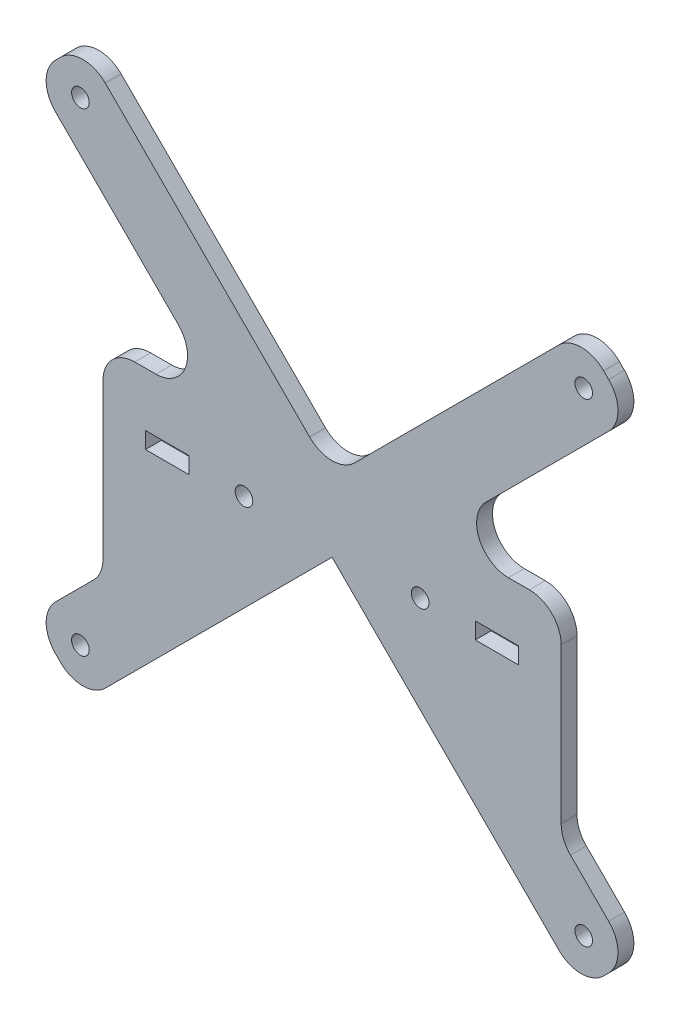
SolidWorks part; units mm, degrees
ref_plane "Front Plane" through (0, 0, 0) normal (0, 0, 1) x (1, 0, 0)
ref_plane "Top Plane" through (0, 0, 0) normal (0, 1, 0) x (1, 0, 0)
ref_plane "Right Plane" through (0, 0, 0) normal (1, 0, 0) x (0, 0, -1)
sketch "Sketch1" plane through (0, 0, 0) normal (0, 0, 1) x (1, 0, 0)
  line L0 (0, -10) -> (-70.7107, -80.7107)
  line L1 (-65, 10) -> (65, 10)
  line L2 (-65, 10) -> (-65, -10)
  line L3 (-65, -10) -> (65, -10)
  line L4 (65, 10) -> (65, -10)
  line L5 (-65, 10) -> (65, -10) construction
  line L6 (-65, -10) -> (65, 10) construction
  line L7 (0, -55) -> (0, 55) construction
  line L8 (-70.7107, -80.7107) -> (-84.8528, -66.5685)
  line L9 (-84.8528, -66.5685) -> (-28.2843, -10)
  line L10 (70.7107, -80.7107) -> (84.8528, -66.5685)
  line L11 (0, -10) -> (70.7107, -80.7107)
  line L12 (84.8528, -66.5685) -> (28.2843, -10)
  line L13 (55, 0) -> (-55, 0) construction
  line L14 (84.8528, 66.5685) -> (28.2843, 10)
  line L15 (0, 10) -> (70.7107, 80.7107)
  line L16 (-84.8528, 66.5685) -> (-28.2843, 10)
  line L17 (0, 10) -> (-70.7107, 80.7107)
  line L18 (70.7107, 80.7107) -> (84.8528, 66.5685)
  line L19 (-70.7107, 80.7107) -> (-84.8528, 66.5685)
  line L20 (-65, -10) -> (-65, -46.7157)
  line L21 (-52.95, -5.3) -> (-40.65, -5.3)
  line L22 (-52.95, -5.3) -> (-52.95, -10)
  line L23 (-52.95, -10) -> (-40.65, -10)
  line L24 (-40.65, -5.3) -> (-40.65, -10)
  line L25 (-52.95, -5.3) -> (-40.65, -10) construction
  line L26 (-52.95, -10) -> (-40.65, -5.3) construction
  line L27 (-6.15, -5.3) -> (6.15, -5.3)
  line L28 (-6.15, -5.3) -> (-6.15, -10)
  line L29 (-6.15, -10) -> (6.15, -10)
  line L30 (6.15, -5.3) -> (6.15, -10)
  line L31 (-6.15, -5.3) -> (6.15, -10) construction
  line L32 (-6.15, -10) -> (6.15, -5.3) construction
  line L33 (40.65, -5.3) -> (52.95, -5.3)
  line L34 (40.65, -5.3) -> (40.65, -10)
  line L35 (40.65, -10) -> (52.95, -10)
  line L36 (52.95, -5.3) -> (52.95, -10)
  line L37 (40.65, -5.3) -> (52.95, -10) construction
  line L38 (40.65, -10) -> (52.95, -5.3) construction
  line L39 (65, -10) -> (65, -46.7157)
  point P0 (0, 0)
  point P24 (-46.8, -7.65)
  point P29 (0, -7.65)
  point P34 (46.8, -7.65)
  dimension "D1" = 130
  dimension "D2" = 20
  dimension "D3" = 45
  dimension "D4" = 100
  dimension "D5" = 20
  dimension "D6" = 12.3
  dimension "D7" = 4.7
  dimension "D8" = 34.5
  dimension "D9" = 34.5
extrude "Boss-Extrude1" add sketch "Sketch1" along normal blind 4.5
sketch "Sketch3" plane through (0, 0, 4.5) normal (0, 0, 1) x (1, 0, 0)
  line L0 (-52.95, -10) -> (-40.65, -10) construction
  line L1 (-52.95, -10) -> (-40.65, -10)
  line L2 (40.65, -10) -> (52.95, -10) construction
  line L3 (40.65, -10) -> (52.95, -10)
  line L16 (84.8528, -66.5685) -> (65, -46.7157)
  line L18 (84.8528, -66.5685) -> (65, -46.7157)
  line L20 (-65, -46.7157) -> (-84.8528, -66.5685)
  line L21 (-65, -46.7157) -> (-84.8528, -66.5685)
  line L26 (-70.7107, -80.7107) -> (0, -10)
  line L27 (0, -10) -> (70.7107, -80.7107)
  line L28 (70.7107, -80.7107) -> (84.8528, -66.5685)
  line L35 (65, -46.7157) -> (65, 10)
  line L36 (65, 10) -> (28.2843, 10)
  line L37 (28.2843, 10) -> (84.8528, 66.5685)
  line L38 (84.8528, 66.5685) -> (70.7107, 80.7107)
  line L39 (70.7107, 80.7107) -> (0, 10)
  line L40 (0, 10) -> (-70.7107, 80.7107)
  line L41 (-70.7107, 80.7107) -> (-84.8528, 66.5685)
  line L42 (-84.8528, 66.5685) -> (-28.2843, 10)
  line L43 (-28.2843, 10) -> (-65, 10)
  line L44 (-65, 10) -> (-65, -46.7157)
  line L51 (-84.8528, -66.5685) -> (-70.7107, -80.7107)
  line L52 (-70.7107, -80.7107) -> (0, -10)
  line L53 (0, -10) -> (70.7107, -80.7107)
  line L54 (70.7107, -80.7107) -> (84.8528, -66.5685)
  line L61 (65, -46.7157) -> (65, 10)
  line L62 (65, 10) -> (28.2843, 10)
  line L63 (28.2843, 10) -> (84.8528, 66.5685)
  line L64 (84.8528, 66.5685) -> (70.7107, 80.7107)
  line L65 (70.7107, 80.7107) -> (0, 10)
  line L66 (0, 10) -> (-70.7107, 80.7107)
  line L67 (-70.7107, 80.7107) -> (-84.8528, 66.5685)
  line L68 (-84.8528, 66.5685) -> (-28.2843, 10)
  line L69 (-28.2843, 10) -> (-65, 10)
  line L70 (-65, 10) -> (-65, -46.7157)
  line L77 (-84.8528, -66.5685) -> (-70.7107, -80.7107)
  circle A0 centre (-25, -7.5) radius 2.5
  circle A1 centre (25, -7.5) radius 2.5
  dimension "D2" = 5
  dimension "D3" = 40
  dimension "D4" = 40
  dimension "D1" = 0
extrude "Cut-Extrude3" cut sketch "Sketch3" against normal through all contours A0 | A1
fillet "Fillet1" radius 9 7 edges at (65, -46.7157, 2.25) (-65, -46.7157, 2.25) (0, 10, 2.25) (28.2843, 10, 2.25) (-28.2843, 10, 2.25) (65, 10, 2.25) (-65, 10, 2.25)
fillet "Fillet2" radius 9 8 edges at (-70.7107, -80.7107, 2.25) (-84.8528, -66.5685, 2.25) (70.7107, -80.7107, 2.25) (84.8528, -66.5685, 2.25) (84.8528, 66.5685, 2.25) (70.7107, 80.7107, 2.25) (-84.8528, 66.5685, 2.25) (-70.7107, 80.7107, 2.25)
sketch "Sketch5" plane through (0, 0, 4.5) normal (0, 0, 1) x (1, 0, 0)
  line L0 (-77.7817, 73.6396) -> (-71.4178, 67.2756) construction
  line L1 (-78.4889, 60.2046) -> (-71.4178, 67.2756) construction
  line L16 (-78.4889, -72.9325) -> (-77.0746, -74.3467)
  line L17 (-64.3467, -74.3467) -> (0, -10)
  line L18 (0, -10) -> (64.3467, -74.3467)
  line L19 (77.0746, -74.3467) -> (78.4889, -72.9325)
  line L20 (78.4889, -60.2046) -> (67.636, -49.3518)
  line L21 (65, -42.9878) -> (65, 1)
  line L22 (56, 10) -> (50.0122, 10)
  line L23 (43.6482, 25.364) -> (78.4889, 60.2046)
  line L24 (78.4889, 72.9325) -> (77.0746, 74.3467)
  line L25 (64.3467, 74.3467) -> (6.364, 16.364)
  line L26 (-6.364, 16.364) -> (-64.3467, 74.3467)
  line L27 (-77.0746, 74.3467) -> (-78.4889, 72.9325)
  line L28 (-78.4889, 60.2046) -> (-43.6482, 25.364)
  line L29 (-50.0122, 10) -> (-56, 10)
  line L30 (-65, 1) -> (-65, -42.9878)
  line L31 (-67.636, -49.3518) -> (-78.4889, -60.2046)
  line L32 (-78.4889, -72.9325) -> (-77.0746, -74.3467)
  line L33 (-64.3467, -74.3467) -> (0, -10)
  line L34 (0, -10) -> (64.3467, -74.3467)
  line L35 (77.0746, -74.3467) -> (78.4889, -72.9325)
  line L36 (78.4889, -60.2046) -> (67.636, -49.3518)
  line L37 (65, -42.9878) -> (65, 1)
  line L38 (56, 10) -> (50.0122, 10)
  line L39 (43.6482, 25.364) -> (78.4889, 60.2046)
  line L40 (78.4889, 72.9325) -> (77.0746, 74.3467)
  line L41 (64.3467, 74.3467) -> (6.364, 16.364)
  line L42 (-6.364, 16.364) -> (-64.3467, 74.3467)
  line L43 (-77.0746, 74.3467) -> (-78.4889, 72.9325)
  line L44 (-78.4889, 60.2046) -> (-43.6482, 25.364)
  line L45 (-50.0122, 10) -> (-56, 10)
  line L46 (-65, 1) -> (-65, -42.9878)
  line L47 (-67.636, -49.3518) -> (-78.4889, -60.2046)
  circle A0 centre (-71.4178, 67.2756) radius 2.5
  arc A19 (-77.0746, -74.3467) -> (-64.3467, -74.3467) centre (-70.7107, -67.9828) ccw
  arc A20 (64.3467, -74.3467) -> (77.0746, -74.3467) centre (70.7107, -67.9828) ccw
  arc A21 (78.4889, -72.9325) -> (78.4889, -60.2046) centre (72.1249, -66.5685) ccw
  arc A22 (65, -42.9878) -> (67.636, -49.3518) centre (74, -42.9878) ccw
  arc A23 (65, 1) -> (56, 10) centre (56, 1) ccw
  arc A24 (43.6482, 25.364) -> (50.0122, 10) centre (50.0122, 19) ccw
  arc A25 (78.4889, 60.2046) -> (78.4889, 72.9325) centre (72.1249, 66.5685) ccw
  arc A26 (77.0746, 74.3467) -> (64.3467, 74.3467) centre (70.7107, 67.9828) ccw
  arc A27 (-6.364, 16.364) -> (6.364, 16.364) centre (0, 22.7279) ccw
  arc A28 (-64.3467, 74.3467) -> (-77.0746, 74.3467) centre (-70.7107, 67.9828) ccw
  arc A29 (-78.4889, 72.9325) -> (-78.4889, 60.2046) centre (-72.1249, 66.5685) ccw
  arc A30 (-50.0122, 10) -> (-43.6482, 25.364) centre (-50.0122, 19) ccw
  arc A31 (-56, 10) -> (-65, 1) centre (-56, 1) ccw
  arc A32 (-67.636, -49.3518) -> (-65, -42.9878) centre (-74, -42.9878) ccw
  arc A33 (-78.4889, -60.2046) -> (-78.4889, -72.9325) centre (-72.1249, -66.5685) ccw
  arc A34 (-77.0746, -74.3467) -> (-64.3467, -74.3467) centre (-70.7107, -67.9828) ccw
  arc A35 (64.3467, -74.3467) -> (77.0746, -74.3467) centre (70.7107, -67.9828) ccw
  arc A36 (78.4889, -72.9325) -> (78.4889, -60.2046) centre (72.1249, -66.5685) ccw
  arc A37 (65, -42.9878) -> (67.636, -49.3518) centre (74, -42.9878) ccw
  arc A38 (65, 1) -> (56, 10) centre (56, 1) ccw
  arc A39 (43.6482, 25.364) -> (50.0122, 10) centre (50.0122, 19) ccw
  arc A40 (78.4889, 60.2046) -> (78.4889, 72.9325) centre (72.1249, 66.5685) ccw
  arc A41 (77.0746, 74.3467) -> (64.3467, 74.3467) centre (70.7107, 67.9828) ccw
  arc A42 (-6.364, 16.364) -> (6.364, 16.364) centre (0, 22.7279) ccw
  arc A43 (-64.3467, 74.3467) -> (-77.0746, 74.3467) centre (-70.7107, 67.9828) ccw
  arc A44 (-78.4889, 72.9325) -> (-78.4889, 60.2046) centre (-72.1249, 66.5685) ccw
  arc A45 (-50.0122, 10) -> (-43.6482, 25.364) centre (-50.0122, 19) ccw
  arc A46 (-56, 10) -> (-65, 1) centre (-56, 1) ccw
  arc A47 (-67.636, -49.3518) -> (-65, -42.9878) centre (-74, -42.9878) ccw
  arc A48 (-78.4889, -60.2046) -> (-78.4889, -72.9325) centre (-72.1249, -66.5685) ccw
  point P11 (0, 0)
  dimension "D1" = 5
  dimension "D2" = 0
extrude "Cut-Extrude4" cut sketch "Sketch5" against normal through all contours A0
mirror "Mirror1" about plane through (0, 0, 0) normal (1, 0, 0) of "Cut-Extrude4"
mirror "Mirror2" about plane through (0, 0, 0) normal (0, 1, 0) of "Mirror1", "Cut-Extrude4"
